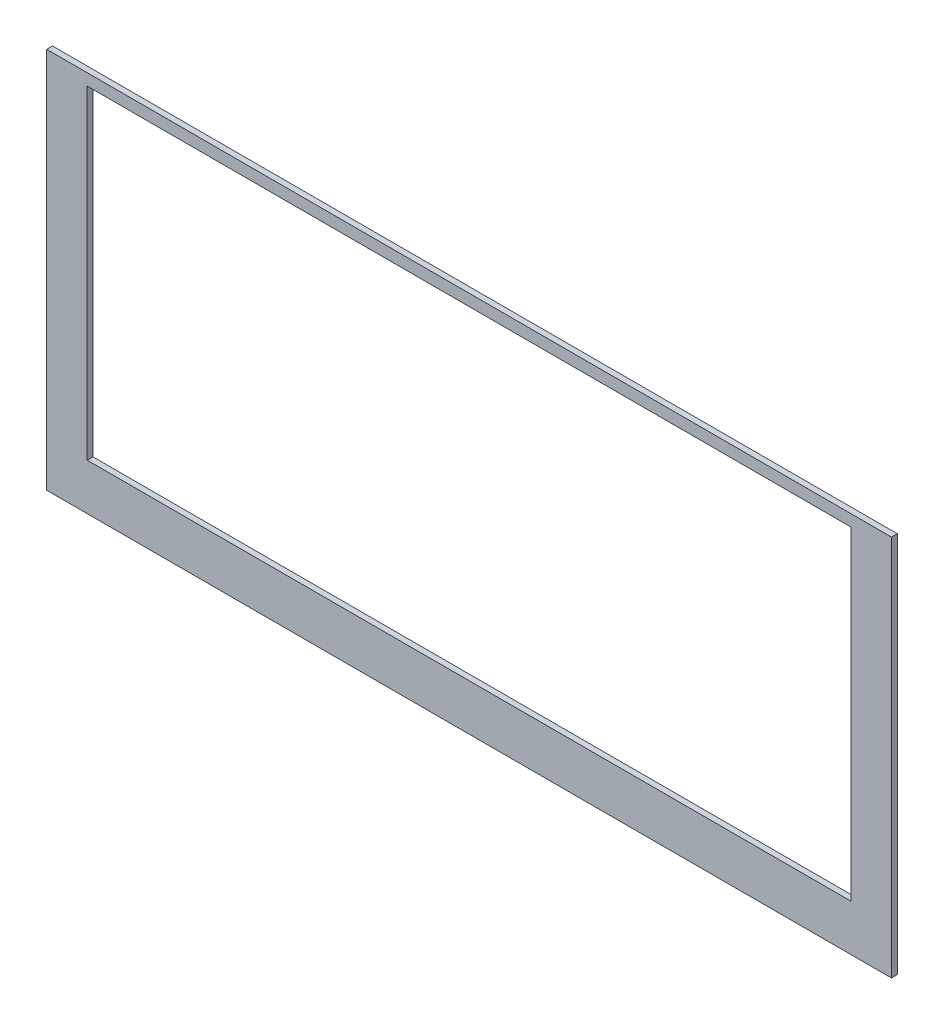
SolidWorks part; units mm, degrees
ref_plane "Alzado" through (0, 0, 0) normal (0, 0, 1) x (1, 0, 0)
ref_plane "Planta" through (0, 0, 0) normal (0, 1, 0) x (1, 0, 0)
ref_plane "Vista lateral" through (0, 0, 0) normal (1, 0, 0) x (0, 0, -1)
sketch "Croquis2" plane through (0, 0, 0) normal (0, 0, 1) x (1, 0, 0)
  line L1 (-365, -165) -> (365, -165)
  line L2 (-365, -165) -> (-365, 165)
  line L3 (-365, 165) -> (365, 165)
  line L4 (365, -165) -> (365, 165)
  line L5 (-365, -165) -> (365, 165) construction
  line L6 (-365, 165) -> (365, -165) construction
  point P0 (0, 0)
  dimension "D1" = 730
  dimension "D2" = 330
extrude "Saliente-Extruir2" add sketch "Croquis2" along normal blind 5
sketch "Croquis4" plane through (0, 0, 5) normal (0, 0, 1) x (1, 0, 0)
  line L0 (365, 165) -> (-365, 165) construction
  line L1 (330, 155) -> (-330, 155)
  line L2 (330, 155) -> (330, -125)
  line L3 (330, -125) -> (-330, -125)
  line L4 (-330, 155) -> (-330, -125)
  line L5 (365, -165) -> (365, 165) construction
  line L6 (-365, 165) -> (-365, -165) construction
  line L7 (-365, -165) -> (365, -165) construction
  dimension "D1" = 10
  dimension "D2" = 35
  dimension "D3" = 35
  dimension "D4" = 40
extrude "Cortar-Extruir1" cut sketch "Croquis4" against normal up to surface (5 mm away) up to face at (0, 0, 0)
